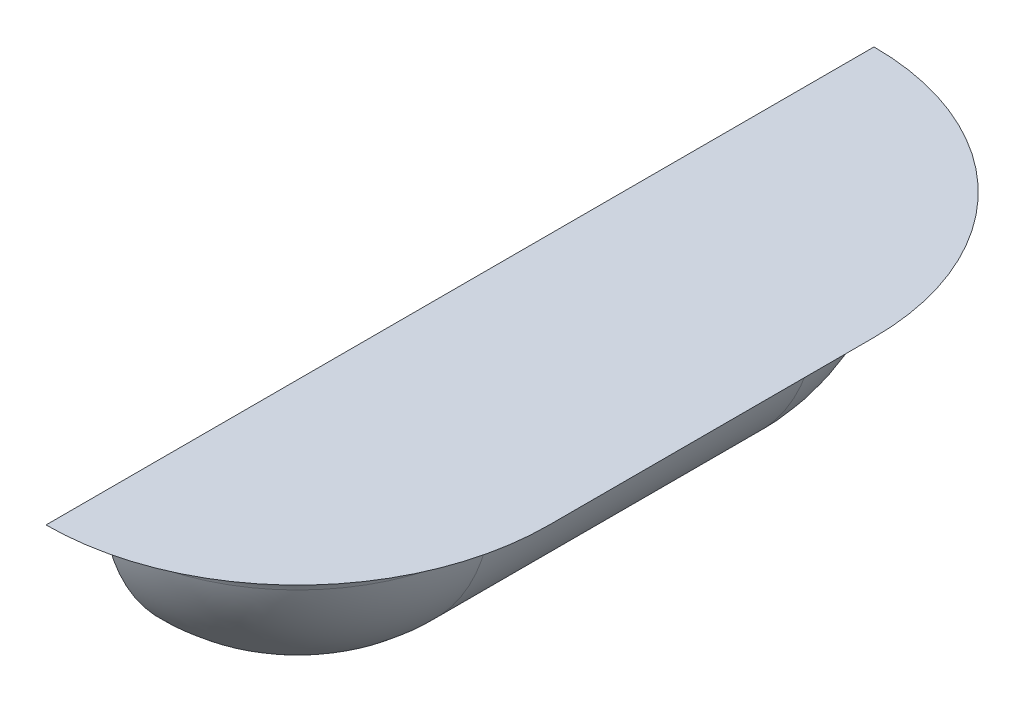
SolidWorks part; units mm, degrees
ref_plane "Plane1" through (0, 0, 0) normal (0, 0, 1) x (1, 0, 0)
ref_plane "Plane2" through (0, 0, 0) normal (0, 1, 0) x (1, 0, 0)
ref_plane "Plane3" through (0, 0, 0) normal (1, 0, 0) x (0, 0, -1)
other "Configuration Table"
sketch "Sketch1" plane through (0, 0, 0) normal (0, 0, 1) x (1, 0, 0)
  line L0 (-15, 0) -> (15, 0)
  line L1 (-15, 0) -> (-15, 3.4642)
  line L2 (15, 3.4642) -> (-15, 3.4642)
  line L3 (15, 3.4642) -> (15, 0)
  line L4 (0, 0) -> (0, 3.4642) construction
  line L5 (50, 0) -> (-50, 0) construction
  dimension "D1" = 30
extrude "Base-Extrude" add sketch "Sketch1" along normal mid plane 50
sketch "Layout Sketch" plane through (0, 0, 0) normal (0, -1, 0) x (1, 0, 0)
  line L0 (-6.5173, 0) -> (7.2244, 0) construction
  line L1 (11.2638, 0) -> (-11.2638, 0) construction
  line L2 (0, 9.1132) -> (0, -7.6236) construction
  line L3 (0, -50) -> (0, 50) construction
  line L9 (-3, -16) -> (-3, 16)
  line L11 (3, 10) -> (3, -10)
  arc A0 (3, 10) -> (-3, 16) centre (-3, 10) ccw
  arc A1 (3, -10) -> (-3, -16) centre (-3, -10) cw
  dimension "Overall width" = 32
  dimension "Depth" = 6
sketch "Louver Body" plane through (0, 0, 0) normal (0, 0, 1) x (1, 0, 0)
  line L0 (-3, 0) -> (-3, -6)
  line L1 (-15, 0) -> (15, 0) construction
  line L2 (-3, 0) -> (3, 0)
  line L4 (3, 0) -> (3, 3.4642) construction
  line L5 (15, 3.4642) -> (-15, 3.4642) construction
  line L6 (-3, -6) -> (-3.0249, -6) construction
  line L8 (0, 3.4642) -> (0, 0) construction
  arc A0 (-3, -6) -> (3, 0) centre (-3, 0) ccw
extrude "Boss-Extrude1" add sketch "Louver Body" along normal mid plane 10
sketch "Sketch12" plane through (0, 0, 5) normal (0, 0, 1) x (1, 0, 0)
  line L0 (-3, 0) -> (-3, -6) construction
  line L1 (-3, 0) -> (-3, -6) construction
  line L2 (-15, 0) -> (15, 0) construction
  line L5 (3, 0) -> (-3, 0)
  line L6 (-3, 0) -> (-3, -6)
  line L7 (3, 0) -> (-3, 0)
  line L8 (-3, 0) -> (-3, -6)
  arc A0 (-3, -6) -> (3, 0) centre (-3, 0) ccw construction
  arc A2 (-3, -6) -> (3, 0) centre (-3, 0) ccw
  arc A3 (-3, -6) -> (3, 0) centre (-3, 0) ccw
  dimension "D1" = 0
revolve "Boss-Revolve2" add sketch "Sketch12" angle 90 about L1
sketch "Sketch13" plane through (0, 0, -5) normal (0, 0, -1) x (-1, 0, 0)
  line L0 (3, -6) -> (3, 0) construction
  line L1 (15, 0) -> (-15, 0) construction
  line L2 (3, 0) -> (-3, 0)
  line L3 (3, -6) -> (3, 0)
  line L4 (3, 0) -> (-3, 0)
  line L5 (3, -6) -> (3, 0)
  arc A1 (-3, 0) -> (3, -6) centre (3, 0) ccw
  arc A2 (-3, 0) -> (3, -6) centre (3, 0) ccw
  dimension "D1" = 0
revolve "Boss-Revolve3" add sketch "Sketch13" angle 90 about L0
fillet "Fillet1" radius 2 3 edges at (1.2426, 0, 9.2426) (3, 0, 0) (1.2426, 0, -9.2426)
sketch "Sketch8" plane through (-15, 0, 0) normal (-1, 0, 0) x (0, 0, 1)
  line L4 (-25, 0) -> (25, 0)
  line L5 (25, 0) -> (25, 3.4642)
  line L6 (25, 3.4642) -> (-25, 3.4642)
  line L7 (-25, 3.4642) -> (-25, 0)
  line L8 (-25, 0) -> (25, 0)
  line L9 (25, 0) -> (25, 3.4642)
  line L10 (25, 3.4642) -> (-25, 3.4642)
  line L11 (-25, 3.4642) -> (-25, 0)
  dimension "D1" = 0
extrude "Cut-Extrude4" cut sketch "Sketch8" against normal through all
sketch "Orientation sketch" plane through (0, 0, 0) normal (0, 1, 0) x (-1, 0, 0)
  line L2 (3, 12.746) -> (3, -12.746)
  line L3 (3, 12.746) -> (3, -12.746)
  line L4 (-4.746, 5) -> (-4.746, -5)
  line L5 (-4.746, 5) -> (-4.746, -5)
  arc A2 (3, 12.746) -> (-4.746, 5) centre (3, 5) ccw
  arc A3 (3, 12.746) -> (-4.746, 5) centre (3, 5) ccw
  arc A4 (-4.746, -5) -> (3, -12.746) centre (3, -5) ccw
  arc A5 (-4.746, -5) -> (3, -12.746) centre (3, -5) ccw
  dimension "D1" = 0
scale "Scale1" [suppressed]
